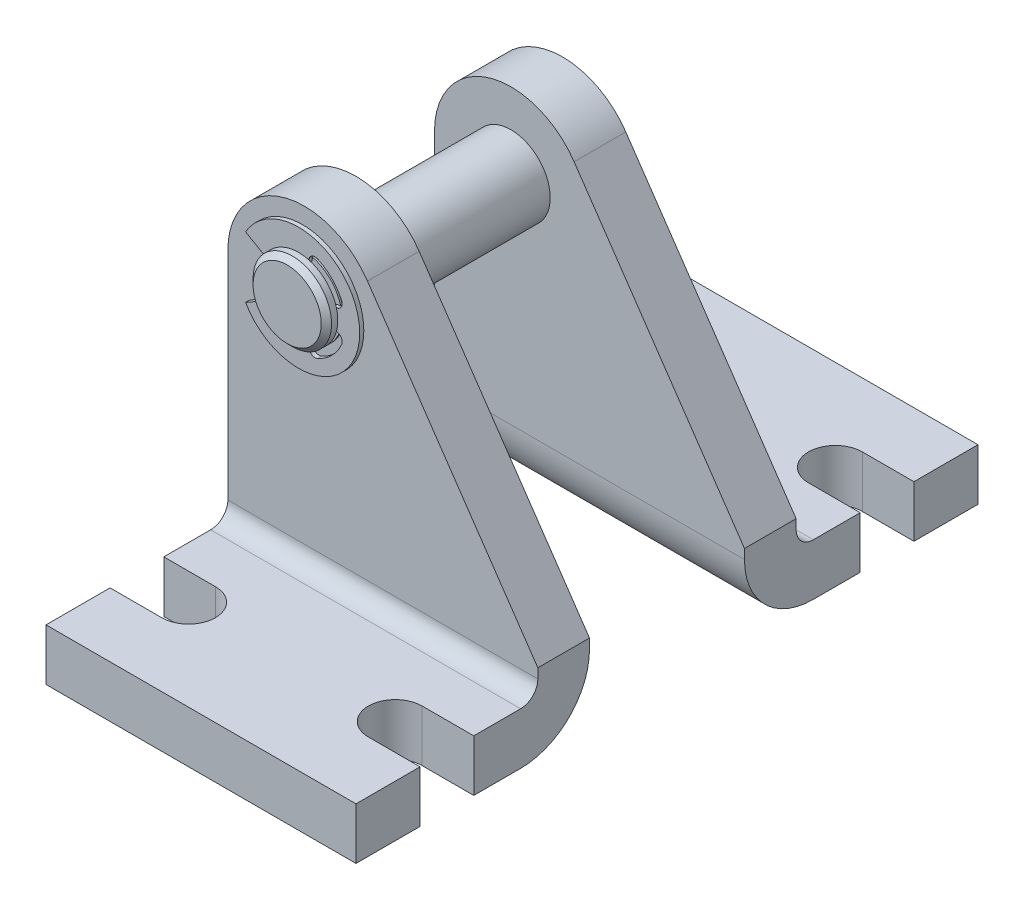
SolidWorks part; units mm, degrees
ref_plane "Front Plane" through (0, 0, 0) normal (0, 0, 1) x (1, 0, 0)
ref_plane "Top Plane" through (0, 0, 0) normal (0, 1, 0) x (1, 0, 0)
ref_plane "Right Plane" through (0, 0, 0) normal (1, 0, 0) x (0, 0, -1)
sketch "Sketch1" plane through (0, 0, 0) normal (0, 0, 1) x (1, 0, 0)
  line L0 (-9.398, 0) -> (-9.398, -35.052)
  line L1 (-9.398, -35.052) -> (28.702, -35.052)
  line L2 (28.702, -35.052) -> (28.702, -25.4)
  line L3 (28.702, -25.4) -> (7.7638, 5.2958)
  line L4 (-9.398, -28.702) -> (28.702, -28.702) construction
  circle A0 centre (0, 0) radius 4.826
  arc A1 (7.7638, 5.2958) -> (-9.398, 0) centre (0, 0) ccw
  point P9 (0, 4.826)
  dimension "Hole" = 9.652
  dimension "Height" = 44.45
  dimension "Vert Height" = 9.652
  dimension "Width" = 38.1
  dimension "Thickness" = 6.35
  dimension "Vert Hole" = 35.052
sketch "Sketch2" plane through (0, 0, 0) normal (0, 1, 0) x (1, 0, 0)
  line L0 (-9.398, -17.526) -> (28.702, -17.526) construction
  line L1 (-9.398, -28.702) -> (28.702, -28.702)
  line L2 (-9.398, -28.702) -> (-9.398, 0)
  line L3 (-9.398, 0) -> (28.702, 0)
  line L4 (28.702, -28.702) -> (28.702, 0)
  line L5 (-3.048, -20.828) -> (-9.398, -20.828)
  line L6 (-3.048, -14.224) -> (-9.398, -14.224)
  line L7 (22.352, -14.224) -> (28.702, -14.224)
  line L8 (22.352, -20.828) -> (28.702, -20.828)
  arc A0 (-3.048, -20.828) -> (-3.048, -14.224) centre (-3.048, -17.526) ccw
  arc A1 (22.352, -14.224) -> (22.352, -20.828) centre (22.352, -17.526) ccw
  dimension "Depth" = 28.702
  dimension "Hole Offset" = 17.526
  dimension "Hole Location" = 25.4
  dimension "Hole Size" = 6.604
sketch "Sketch3" plane through (0, 0, 0) normal (0, 0, 1) x (1, 0, 0)
  line L0 (-9.398, 0) -> (-9.398, -35.052) construction
  line L1 (28.702, -25.4) -> (7.7638, 5.2958) construction
  line L2 (28.702, -35.052) -> (28.702, -25.4) construction
  line L3 (-9.398, -35.052) -> (28.702, -35.052) construction
  line L4 (-9.398, 0) -> (-9.398, -35.052)
  line L5 (28.702, -25.4) -> (7.7638, 5.2958)
  line L6 (28.702, -35.052) -> (28.702, -25.4)
  line L7 (-9.398, -35.052) -> (28.702, -35.052)
  arc A0 (7.7638, 5.2958) -> (-9.398, 0) centre (0, 0) ccw construction
  circle A1 centre (0, 0) radius 4.826 construction
  arc A2 (7.7638, 5.2958) -> (-9.398, 0) centre (0, 0) ccw
  circle A3 centre (0, 0) radius 4.826
extrude "Boss-Extrude1" add sketch "Sketch3" along normal blind 6.35
sketch "Sketch4" plane through (0, 0, 6.35) normal (0, 0, 1) x (1, 0, 0)
  line L1 (-9.398, -35.052) -> (28.702, -35.052)
  line L2 (-9.398, -35.052) -> (-9.398, -28.702)
  line L3 (-9.398, -28.702) -> (28.702, -28.702)
  line L4 (28.702, -35.052) -> (28.702, -28.702)
extrude "Boss-Extrude2" add sketch "Sketch4" along normal up to vertex (22.352 mm away) up to point (-9.398, 0, 28.702)
sketch "Sketch5" plane through (0, -28.702, 0) normal (0, 1, 0) x (1, 0, 0)
  line L0 (-3.048, -20.828) -> (-9.398, -20.828) construction
  line L1 (-3.048, -14.224) -> (-9.398, -14.224) construction
  line L2 (22.352, -14.224) -> (28.702, -14.224) construction
  line L3 (22.352, -20.828) -> (28.702, -20.828) construction
  line L4 (-3.048, -20.828) -> (-9.398, -20.828)
  line L5 (-3.048, -14.224) -> (-9.398, -14.224)
  line L6 (22.352, -14.224) -> (28.702, -14.224)
  line L7 (22.352, -20.828) -> (28.702, -20.828)
  line L8 (-9.398, -20.828) -> (-9.398, -14.224)
  line L9 (28.702, -20.828) -> (28.702, -14.224)
  arc A0 (-3.048, -20.828) -> (-3.048, -14.224) centre (-3.048, -17.526) ccw construction
  arc A1 (22.352, -14.224) -> (22.352, -20.828) centre (22.352, -17.526) ccw construction
  arc A2 (-3.048, -20.828) -> (-3.048, -14.224) centre (-3.048, -17.526) ccw
  arc A3 (22.352, -14.224) -> (22.352, -20.828) centre (22.352, -17.526) ccw
extrude "Cut-Extrude1" cut sketch "Sketch5" against normal through all
fillet "Fillet1" radius 2.1167 1 edges
fillet "Fillet2" radius 8.4667 1 edges at (9.652, -35.052, 0)
ref_plane "Plane1" through (0, 0, -9.525) normal (0, 0, 1) x (1, 0, 0)
mirror "Mirror2" about plane through (0, 0, -9.525) normal (0, 0, 1) of bodies 103
sketch "Sketch6" plane through (0, 0, 0) normal (1, 0, 0) x (0, 0, -1)
  line L0 (-8.4582, 0) -> (27.5082, 0)
  line L1 (27.5082, 0) -> (27.5082, 4.191)
  line L2 (27.5082, 4.191) -> (26.8732, 4.826)
  line L3 (26.8732, 4.826) -> (26.1112, 4.826)
  line L4 (26.1112, 4.826) -> (26.1112, 4.064)
  line L5 (26.1112, 4.064) -> (25.6032, 4.064)
  line L6 (25.6032, 4.064) -> (25.6032, 4.826)
  line L7 (25.6032, 4.826) -> (-6.5532, 4.826)
  line L8 (-6.5532, 4.826) -> (-6.5532, 4.064)
  line L9 (-6.5532, 4.064) -> (-7.0612, 4.064)
  line L10 (-7.0612, 4.064) -> (-7.0612, 4.826)
  line L11 (-7.0612, 4.826) -> (-7.8232, 4.826)
  line L12 (-7.8232, 4.826) -> (-8.4582, 4.191)
  line L13 (-8.4582, 4.191) -> (-8.4582, 0)
  line L16 (-6.35, -25.4) -> (-6.35, 5.2958) construction
  line L17 (25.4, 0) -> (25.4, 9.398) construction
  dimension "D1" = 0.2032
  dimension "D2" = 45
  dimension "D3" = 0.508
  dimension "D4" = 0.762
  dimension "D5" = 0.635
  dimension "D6" = 0.762
  dimension "D7" = 0.2032
revolve "Revolve1" add sketch "Sketch6" angle 360 mid plane about L0
sketch "Sketch7" plane through (0, 0, -25.6032) normal (0, 0, -1) x (-1, 0, 0)
  line L0 (3.5195, 2.032) -> (6.5111, 3.7592)
  line L1 (3.5195, -2.032) -> (6.5111, -3.7592)
  line L2 (0, 0) -> (7.5184, 0) construction
  line L3 (0, 4.064) -> (0, 7.5184) construction
  line L4 (-1.2866, 4.8018) -> (-1.0518, 3.9255)
  line L5 (-3.9255, 1.0518) -> (-4.8018, 1.2866)
  line L6 (-3.9255, -1.0518) -> (-4.8018, -1.2866)
  line L7 (-1.2866, -4.8018) -> (-1.0518, -3.9255)
  line L8 (0, 0) -> (-4.095, 4.095) construction
  line L9 (0, 0) -> (-9.398, 0) construction
  circle A0 centre (0, 0) radius 4.064 construction
  arc A1 (3.5195, 2.032) -> (-1.0518, 3.9255) centre (0, 0) ccw
  arc A2 (6.5111, 3.7592) -> (6.5111, -3.7592) centre (0, 0) ccw
  arc A3 (-2.3291, 5.3022) -> (-5.3022, 2.3291) centre (0, 0) ccw
  arc A4 (-5.3022, -2.3291) -> (-2.3291, -5.3022) centre (0, 0) ccw
  arc A5 (-1.2866, -4.8018) -> (-2.3291, -5.3022) centre (-2.0227, -4.6045) cw
  arc A6 (-4.8018, -1.2866) -> (-5.3022, -2.3291) centre (-4.6045, -2.0227) ccw
  arc A7 (-4.8018, 1.2866) -> (-5.3022, 2.3291) centre (-4.6045, 2.0227) cw
  arc A8 (-1.2866, 4.8018) -> (-2.3291, 5.3022) centre (-2.0227, 4.6045) ccw
  arc A9 (9.398, 0) -> (-7.7638, 5.2958) centre (0, 0) ccw construction
  arc A10 (-3.9255, 1.0518) -> (-3.9255, -1.0518) centre (0, 0) ccw
  circle A11 centre (0, 0) radius 4.064 construction
  arc A12 (-1.0518, -3.9255) -> (3.5195, -2.032) centre (0, 0) ccw
  circle A14 centre (0, 0) radius 7.5184 construction
  point P2 (8.128, 0)
  point P12 (0, 5.7912)
  point P23 (-1.4989, -5.5939)
  point P26 (-5.5939, -1.4989)
  point P29 (-5.5939, 1.4989)
  point P32 (-1.4989, 5.5939)
  point P33 (-4.095, 4.095)
  point P35 (3.8864, 1.1882)
  dimension "D4" = 0.762
  dimension "D6" = 7.5184
  dimension "D2" = 60
  dimension "D3" = 60
  dimension "D5" = 45
  dimension "D1" = 9.398
extrude "Boss-Extrude3" add sketch "Sketch7" along normal blind 0.508
mirror "Mirror3" about plane through (0, 0, -9.525) normal (0, 0, 1) of "Boss-Extrude3"
equation "\"D1@Boss-Extrude1\" = \"Thickness@Sketch1\""
equation "\"D1@Fillet1\" = \"Thickness@Sketch1\"/3"
equation "\"D1@Fillet2\" = \"Thickness@Sketch1\"+\"D1@Fillet1\""
equation "\"D6@Sketch7\" = \"D1@Sketch7\"*.8"
